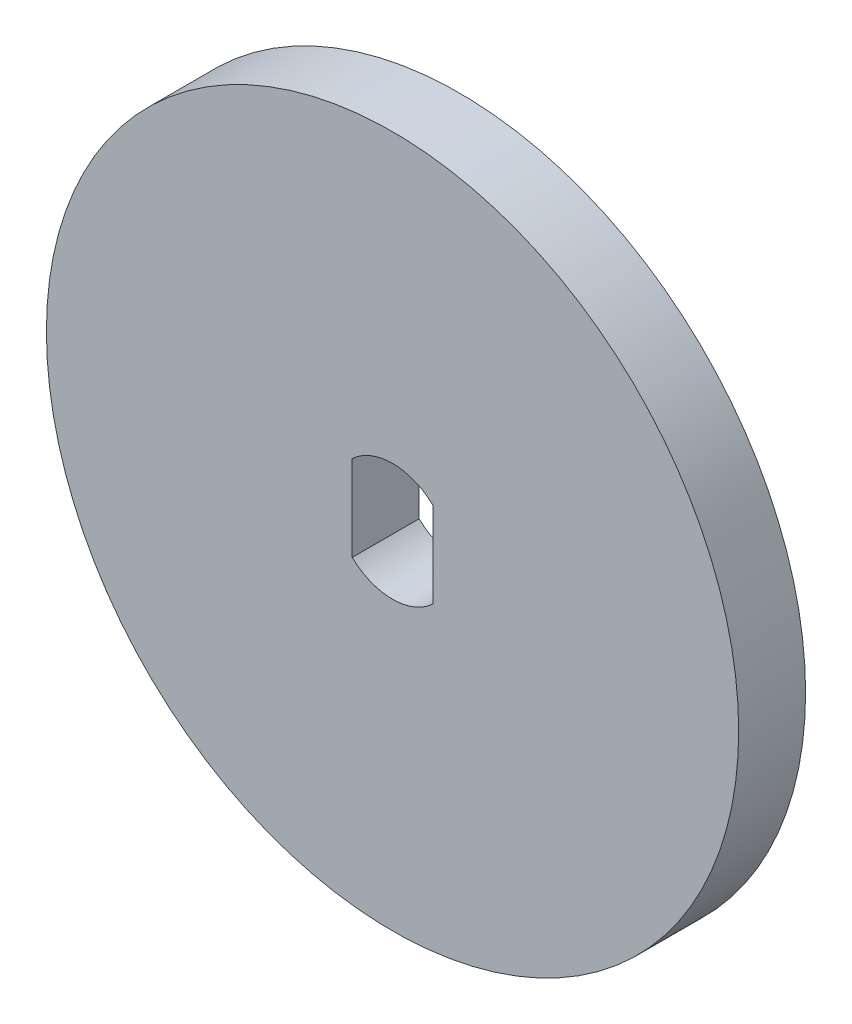
SolidWorks part; units mm, degrees
ref_plane "Front Plane" through (0, 0, 0) normal (0, 0, 1) x (1, 0, 0)
ref_plane "Top Plane" through (0, 0, 0) normal (0, 1, 0) x (1, 0, 0)
ref_plane "Right Plane" through (0, 0, 0) normal (1, 0, 0) x (0, 0, -1)
sketch "Sketch1" plane through (0, 0, 0) normal (0, 0, 1) x (1, 0, 0)
  line L2 (1.75, -1.8547) -> (1.75, 1.8547)
  line L4 (-1.75, -1.8547) -> (-1.75, 1.8547)
  line L5 (1.75, -1.8547) -> (-1.75, 1.8547) construction
  line L6 (1.75, 1.8547) -> (-1.75, -1.8547) construction
  arc A0 (-1.75, -1.8547) -> (1.75, -1.8547) centre (0, 0) ccw
  circle A1 centre (0, 0) radius 15
  arc A2 (1.75, 1.8547) -> (-1.75, 1.8547) centre (0, 0) ccw
  dimension "D1" = 3.5
  dimension "D2" = 2.55
  dimension "D3" = 30
extrude "Boss-Extrude1" add sketch "Sketch1" along normal mid plane 2.9
